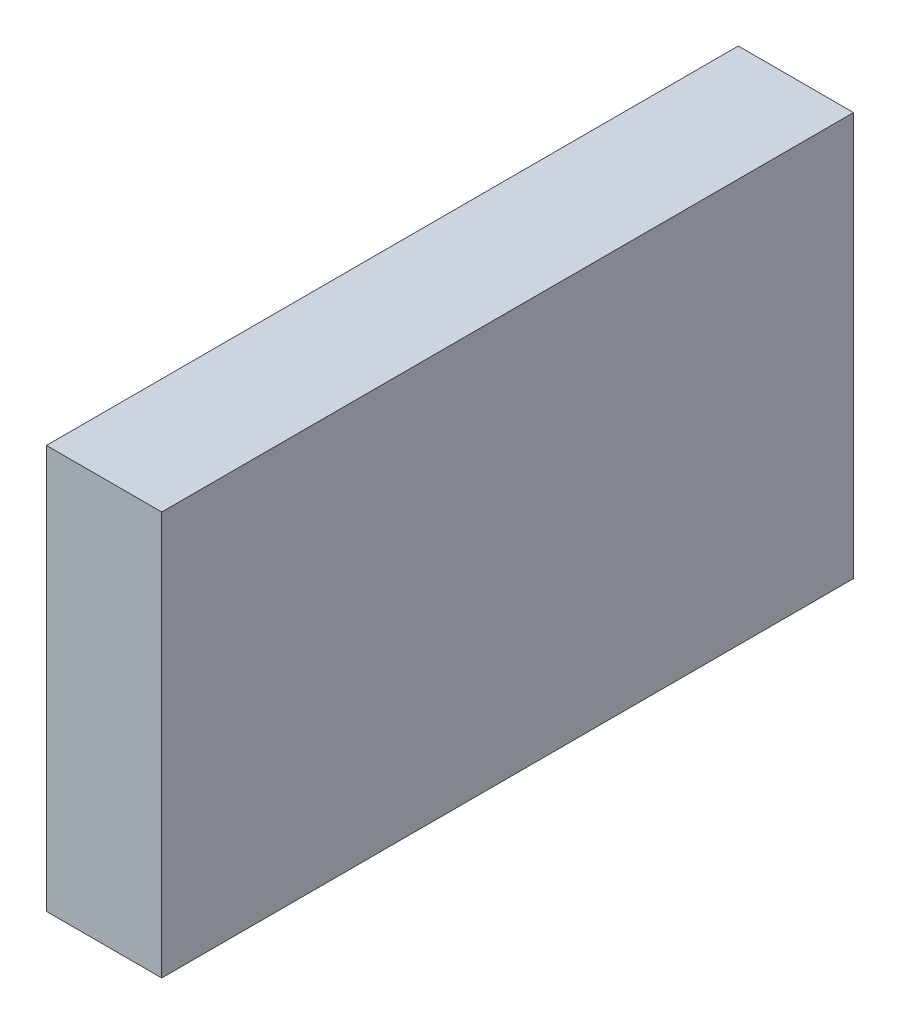
SolidWorks part; units mm, degrees
ref_plane "Front Plane" through (0, 0, 0) normal (0, 0, 1) x (1, 0, 0)
ref_plane "Top Plane" through (0, 0, 0) normal (0, 1, 0) x (1, 0, 0)
ref_plane "Right Plane" through (0, 0, 0) normal (1, 0, 0) x (0, 0, -1)
sketch "Sketch1" plane through (0, 0, 0) normal (0, 0, 1) x (1, 0, 0)
  line L1 (25.4, -88.9) -> (-25.4, -88.9)
  line L2 (25.4, -88.9) -> (25.4, 88.9)
  line L3 (25.4, 88.9) -> (-25.4, 88.9)
  line L4 (-25.4, -88.9) -> (-25.4, 88.9)
  line L5 (25.4, -88.9) -> (-25.4, 88.9) construction
  line L6 (25.4, 88.9) -> (-25.4, -88.9) construction
  point P0 (0, 0)
  dimension "D1" = 177.8
  dimension "D2" = 50.8
extrude "Boss-Extrude1" add sketch "Sketch1" along normal blind 304.8
